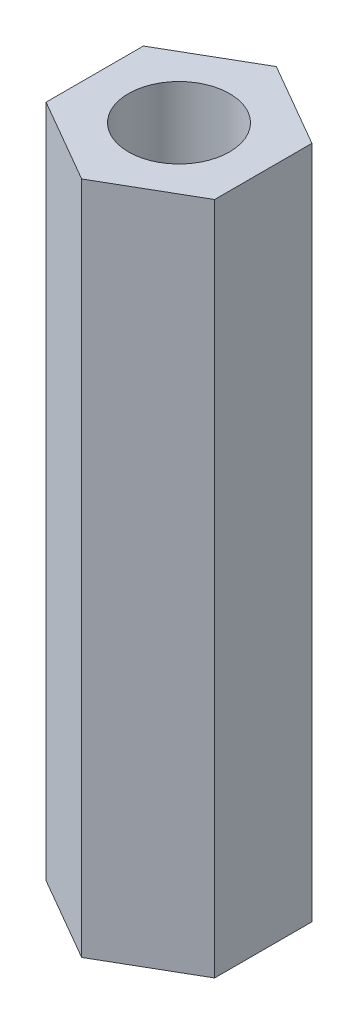
SolidWorks part; units mm, degrees
ref_plane "前基準面" through (0, 0, 0) normal (0, 0, 1) x (1, 0, 0)
ref_plane "上基準面" through (0, 0, 0) normal (0, 1, 0) x (1, 0, 0)
ref_plane "右基準面" through (0, 0, 0) normal (1, 0, 0) x (0, 0, -1)
sketch "草圖1" plane through (0, 0, 0) normal (0, 1, 0) x (1, 0, 0)
  line L1 (0, 2.8868) -> (-2.5, 1.4434)
  line L2 (-2.5, 1.4434) -> (-2.5, -1.4434)
  line L3 (-2.5, -1.4434) -> (0, -2.8868)
  line L4 (0, -2.8868) -> (2.5, -1.4434)
  line L5 (2.5, -1.4434) -> (2.5, 1.4434)
  line L6 (2.5, 1.4434) -> (0, 2.8868)
  circle A0 centre (0, 0) radius 2.5 construction
  dimension "D1" = 5
extrude "填料-伸長1" add sketch "草圖1" along normal blind 20
sketch "草圖2" plane through (0, 20, 0) normal (0, 1, 0) x (-1, 0, 0)
  circle A0 centre (0, 0) radius 1.5
  dimension "D1" = 3
extrude "除料-伸長1" cut sketch "草圖2" against normal up to next
